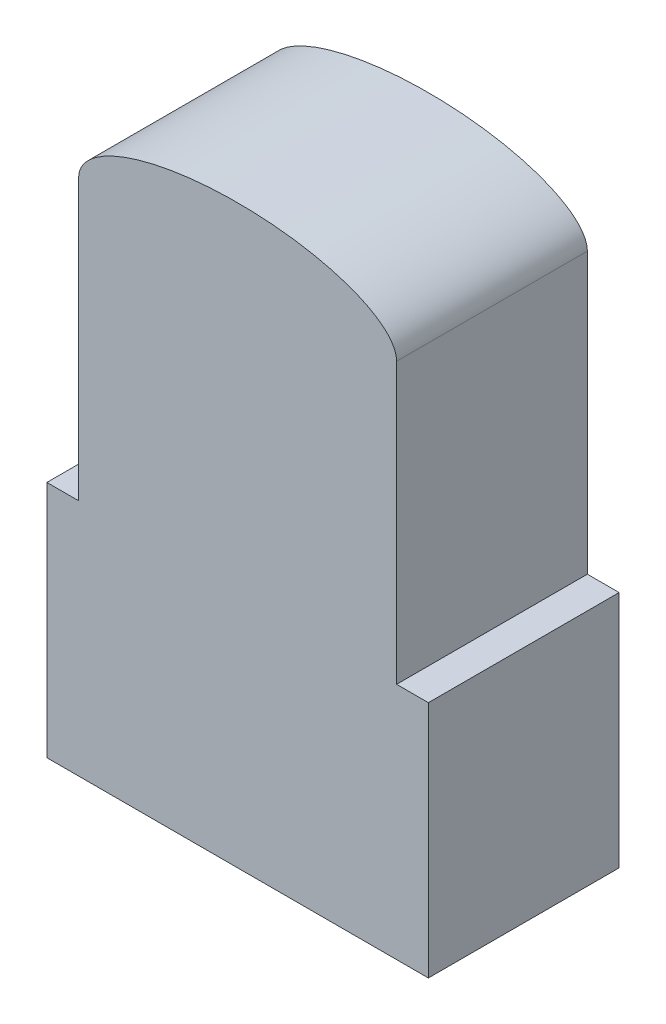
SolidWorks part; units mm, degrees
ref_plane "Alzado" through (0, 0, 0) normal (0, 0, 1) x (1, 0, 0)
ref_plane "Planta" through (0, 0, 0) normal (0, 1, 0) x (1, 0, 0)
ref_plane "Vista lateral" through (0, 0, 0) normal (1, 0, 0) x (0, 0, -1)
sketch "Model" plane through (0, 0, 0) normal (0, 0, 1) x (1, 0, 0)
  line L0 (175.3787, 141.5356) -> (175.3787, 137.1356)
  line L1 (180.3787, 137.1356) -> (180.3787, 141.5356)
  line L2 (175.3787, 137.1356) -> (174.8787, 137.1356)
  line L3 (174.8787, 137.1356) -> (174.8787, 133.3856)
  line L4 (174.8787, 133.3856) -> (180.8787, 133.3856)
  line L5 (180.8787, 133.3856) -> (180.8787, 137.1356)
  line L6 (180.8787, 137.1356) -> (180.3787, 137.1356)
  ellipse E0 centre (177.8787, 141.5356) end of major axis (180.3787, 141.5356) minor radius 0.9095 (180.3787, 141.5356) -> (175.3787, 141.5356) ccw
extrude "Saliente-Extruir1" add sketch "Model" along normal blind 3
